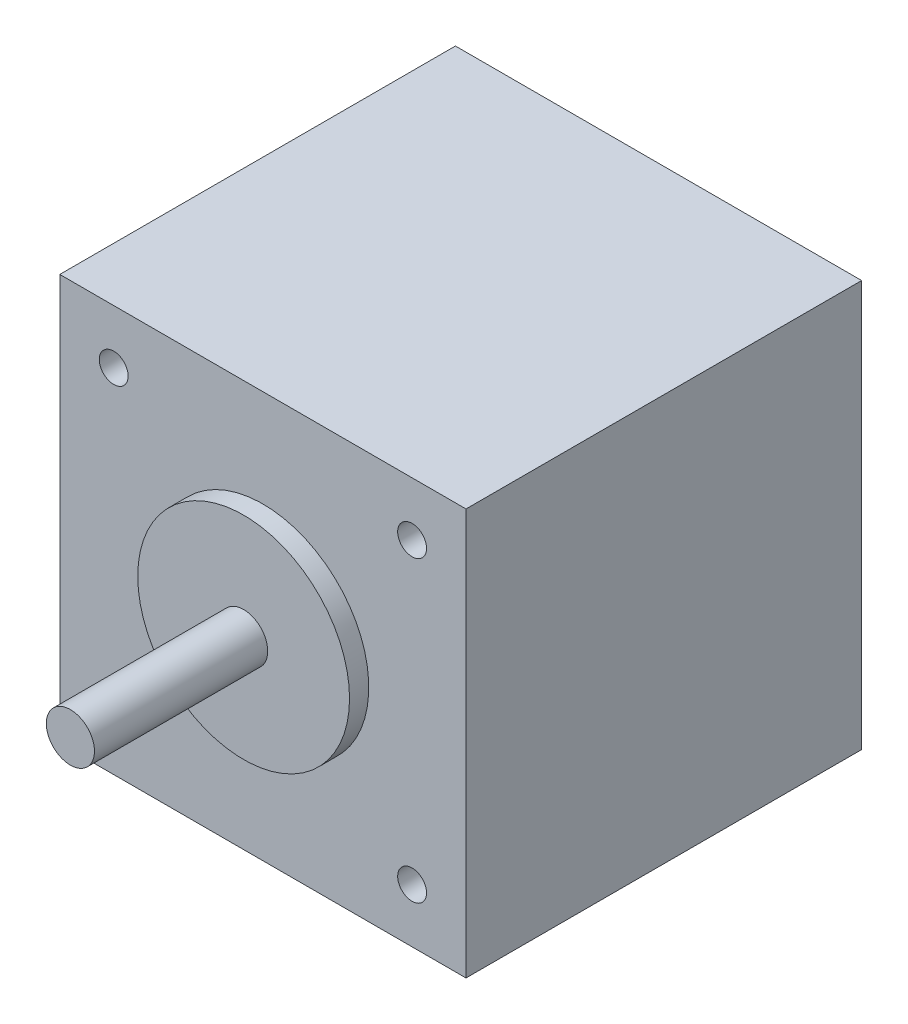
SolidWorks part; units mm, degrees
ref_plane "Plan de face" through (0, 0, 0) normal (0, 0, 1) x (1, 0, 0)
ref_plane "Plan de dessus" through (0, 0, 0) normal (0, 1, 0) x (1, 0, 0)
ref_plane "Plan de droite" through (0, 0, 0) normal (1, 0, 0) x (0, 0, -1)
sketch "Esquisse1" plane through (0, 0, 0) normal (0, 0, 1) x (1, 0, 0)
  line L1 (28.1236, 25.5227) -> (-14.0764, 25.5227)
  line L2 (28.1236, 25.5227) -> (28.1236, -16.6773)
  line L3 (28.1236, -16.6773) -> (-14.0764, -16.6773)
  line L4 (-14.0764, 25.5227) -> (-14.0764, -16.6773)
  dimension "D1" = 42.2
  dimension "D2" = 42.2
extrude "Extrusion1" add sketch "Esquisse1" along normal blind 41.1
sketch "Esquisse2" plane through (0, 0, 41.1) normal (0, 0, 1) x (1, 0, 0)
  line L0 (28.1236, -16.6773) -> (28.1236, 25.5227) construction
  line L1 (28.1236, 25.5227) -> (-14.0764, 25.5227) construction
  circle A0 centre (7.0236, 4.4227) radius 11
  dimension "D1" = 21.1
  dimension "D2" = 21.1
extrude "Extrusion2" add sketch "Esquisse2" along normal blind 2
sketch "Esquisse3" plane through (0, 0, 43.1) normal (0, 0, 1) x (1, 0, 0)
  line L0 (28.1236, -16.6773) -> (28.1236, 25.5227) construction
  line L1 (28.1236, 25.5227) -> (-14.0764, 25.5227) construction
  circle A0 centre (7.0236, 4.4227) radius 2.5
  point P2 (28.1236, 4.4227)
  dimension "D1" = 21.1
  dimension "D2" = 21.1
extrude "Extrusion3" add sketch "Esquisse3" along normal blind 18
sketch "Esquisse4" plane through (0, 0, 41.1) normal (0, 0, 1) x (1, 0, 0)
  line L0 (7.0236, 25.5227) -> (7.0236, -16.6773) construction
  line L1 (28.1236, 25.5227) -> (-14.0764, 25.5227) construction
  line L2 (-14.0764, -16.6773) -> (28.1236, -16.6773) construction
  line L3 (28.1236, 4.4227) -> (-14.0764, 4.4227) construction
  line L4 (28.1236, -16.6773) -> (28.1236, 25.5227) construction
  line L5 (-14.0764, 25.5227) -> (-14.0764, -16.6773) construction
  circle A0 centre (-8.4764, 19.9227) radius 1.5
  circle A1 centre (22.5236, 19.9227) radius 1.5
  circle A2 centre (22.5236, -11.0773) radius 1.5
  circle A3 centre (-8.4764, -11.0773) radius 1.5
  dimension "D1" = 15.5
  dimension "D2" = 15.5
extrude "Extrusion4" cut sketch "Esquisse4" against normal blind 4
